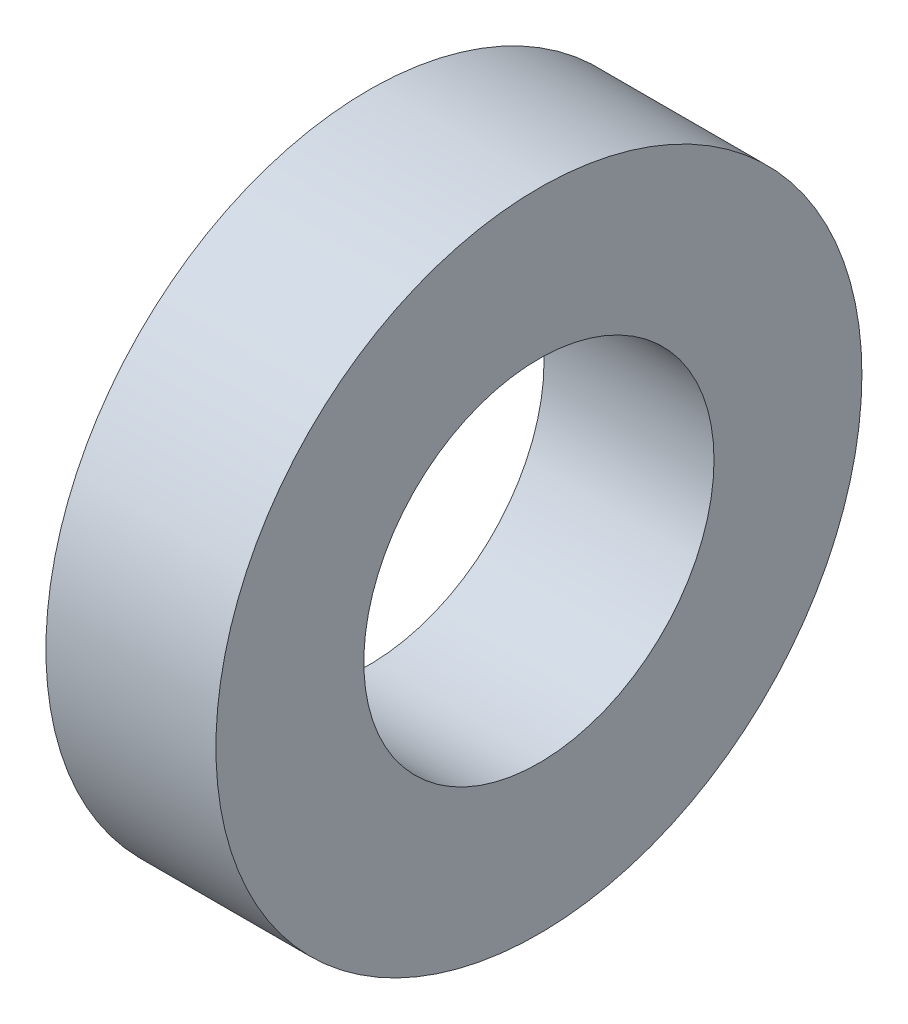
SolidWorks part; units mm, degrees
material "Plain Carbon Steel"
ref_plane "Front Plane" through (0, 0, 0) normal (0, 0, 1) x (1, 0, 0)
ref_plane "Top Plane" through (0, 0, 0) normal (0, 1, 0) x (1, 0, 0)
ref_plane "Right Plane" through (0, 0, 0) normal (1, 0, 0) x (0, 0, -1)
sketch "Sketch1" plane through (0, 0, 0) normal (1, 0, 0) x (0, 0, -1)
  circle A0 centre (0, 0) radius 25.75
  circle A1 centre (0, 0) radius 47.5
  dimension "D1" = 51.5
  dimension "D2" = 95
extrude "Boss-Extrude1" add sketch "Sketch1" along normal blind 25
